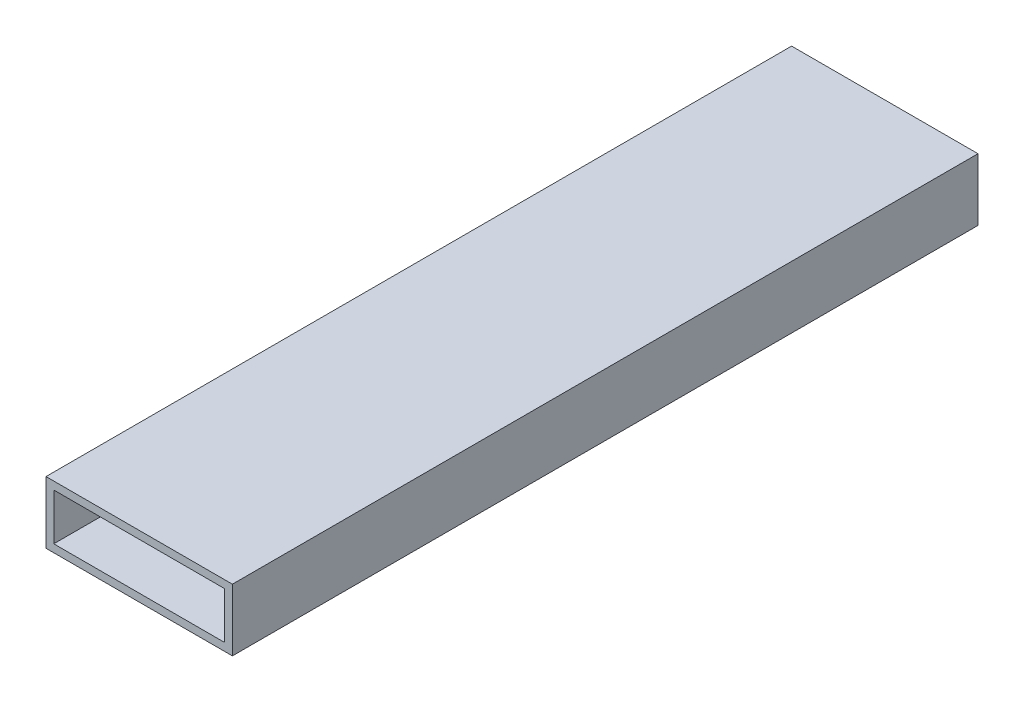
SolidWorks part; units mm, degrees
ref_plane "Front Plane" through (0, 0, 0) normal (0, 0, 1) x (1, 0, 0)
ref_plane "Top Plane" through (0, 0, 0) normal (0, 1, 0) x (1, 0, 0)
ref_plane "Right Plane" through (0, 0, 0) normal (1, 0, 0) x (0, 0, -1)
sketch "Sketch1" plane through (0, 0, 0) normal (0, 0, 1) x (1, 0, 0)
  line L1 (-38.1, 12.7) -> (38.1, 12.7)
  line L2 (-38.1, 12.7) -> (-38.1, -12.7)
  line L3 (-38.1, -12.7) -> (38.1, -12.7)
  line L4 (38.1, 12.7) -> (38.1, -12.7)
  line L5 (-38.1, 12.7) -> (38.1, -12.7) construction
  line L6 (-38.1, -12.7) -> (38.1, 12.7) construction
  point P0 (0, 0)
  dimension "D1" = 76.2
  dimension "D2" = 25.4
extrude "Extrude1" add sketch "Sketch1" against normal mid plane 304.8
sketch "Sketch2" plane through (0, 0, 152.4) normal (0, 0, 1) x (1, 0, 0)
  line L8 (34.925, -9.525) -> (34.925, 9.525)
  line L9 (34.925, 9.525) -> (-34.925, 9.525)
  line L10 (-34.925, 9.525) -> (-34.925, -9.525)
  line L11 (-34.925, -9.525) -> (34.925, -9.525)
  line L12 (34.925, -9.525) -> (34.925, 9.525)
  line L13 (34.925, 9.525) -> (-34.925, 9.525)
  line L14 (-34.925, 9.525) -> (-34.925, -9.525)
  line L15 (-34.925, -9.525) -> (34.925, -9.525)
  dimension "D1" = 3.175
extrude "Extrude2" cut sketch "Sketch2" against normal through all
